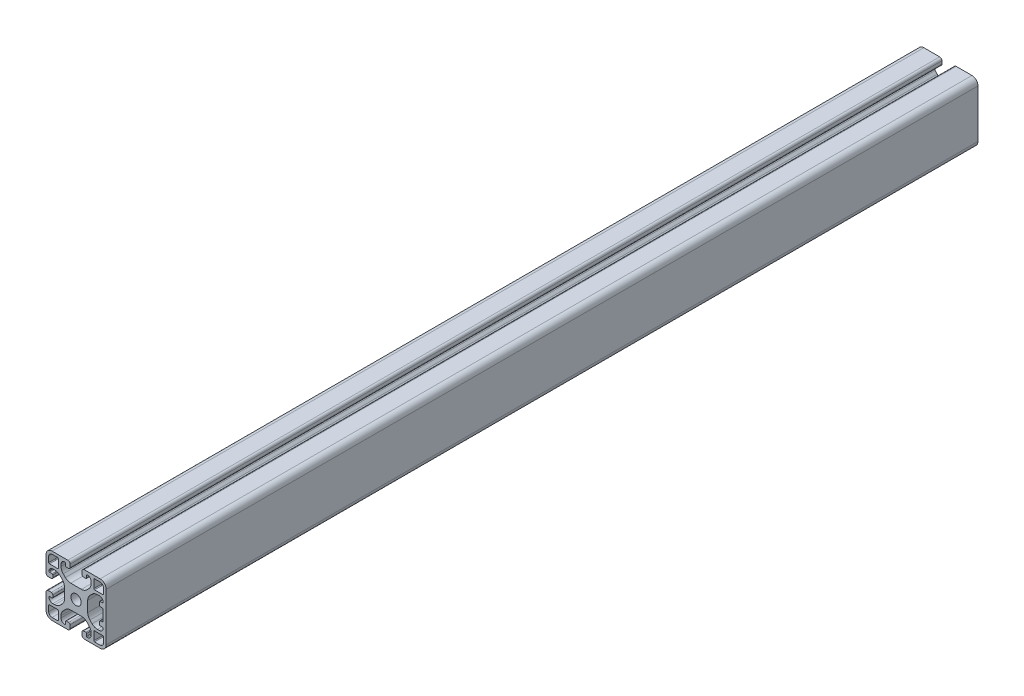
SolidWorks part; units mm, degrees
ref_plane "Piano frontale" through (0, 0, 0) normal (0, 0, 1) x (1, 0, 0)
ref_plane "Piano superiore" through (0, 0, 0) normal (0, 1, 0) x (1, 0, 0)
ref_plane "Piano destro" through (0, 0, 0) normal (1, 0, 0) x (0, 0, -1)
ref_plane "Piano1" through (0, 0, -340) normal (0, 0, -1) x (-1, 0, 0)
sketch "Schizzo1" plane through (0, 0, -340) normal (0, 0, -1) x (-1, 0, 0)
  line L0 (-12.3, -18.2) -> (-16, -18.2)
  line L1 (-18.2, -16) -> (-18.2, -12.3)
  line L2 (-17.7, -11.8) -> (-12.3, -11.8)
  line L3 (-11.8, -12.3) -> (-11.8, -17.7)
  line L4 (-11.8, 17.7) -> (-11.8, 12.3)
  line L5 (-12.3, 11.8) -> (-17.7, 11.8)
  line L6 (-18.2, 12.3) -> (-18.2, 16)
  line L7 (-16, 18.2) -> (-12.3, 18.2)
  line L8 (18.2, 16) -> (18.2, 12.3)
  line L9 (17.7, 11.8) -> (12.3, 11.8)
  line L10 (11.8, 12.3) -> (11.8, 17.7)
  line L11 (12.3, 18.2) -> (16, 18.2)
  line L12 (6.5, -15.5) -> (5, -15.5)
  line L13 (4, -16.5) -> (4, -18.5)
  line L14 (5.5, -20) -> (16, -20)
  line L15 (20, -16) -> (20, -5.5)
  line L16 (18.5, -4) -> (16.5, -4)
  line L17 (15.5, -5) -> (15.5, -6.5)
  line L18 (16, -7) -> (17.55, -7)
  line L19 (18, -7.45) -> (18, -7.5)
  line L20 (15.5, -10) -> (14.1924, -10)
  line L21 (10.6569, -8.5355) -> (9.2145, -7.0931)
  line L22 (7.75, -3.5576) -> (7.75, 3.5576)
  line L23 (9.2145, 7.0931) -> (10.6569, 8.5355)
  line L24 (14.1924, 10) -> (15.5, 10)
  line L25 (18, 7.5) -> (18, 7.45)
  line L26 (17.55, 7) -> (16, 7)
  line L27 (15.5, 6.5) -> (15.5, 5)
  line L28 (16.5, 4) -> (18.5, 4)
  line L29 (20, 5.5) -> (20, 16)
  line L30 (16, 20) -> (5.5, 20)
  line L31 (4, 18.5) -> (4, 16.5)
  line L32 (5, 15.5) -> (6.5, 15.5)
  line L33 (7, 16) -> (7, 17.55)
  line L34 (7.45, 18) -> (7.5, 18)
  line L35 (10, 15.5) -> (10, 14.1924)
  line L36 (8.5355, 10.6569) -> (7.0931, 9.2145)
  line L37 (3.5576, 7.75) -> (-3.5576, 7.75)
  line L38 (-7.0931, 9.2145) -> (-8.5355, 10.6569)
  line L39 (-10, 14.1924) -> (-10, 15.5)
  line L40 (-7.5, 18) -> (-7.45, 18)
  line L41 (-7, 17.55) -> (-7, 16)
  line L42 (-6.5, 15.5) -> (-5, 15.5)
  line L43 (-4, 16.5) -> (-4, 18.5)
  line L44 (-5.5, 20) -> (-16, 20)
  line L45 (-20, 16) -> (-20, -16)
  line L46 (-16, -20) -> (-5.5, -20)
  line L47 (-4, -18.5) -> (-4, -16.5)
  line L48 (-5, -15.5) -> (-6.5, -15.5)
  line L49 (-7, -16) -> (-7, -17.55)
  line L50 (-7.45, -18) -> (-7.5, -18)
  line L51 (-10, -15.5) -> (-10, -14.1924)
  line L52 (-8.5355, -10.6569) -> (-7.0931, -9.2145)
  line L53 (-3.5576, -7.75) -> (3.5576, -7.75)
  line L54 (7.0931, -9.2145) -> (8.5355, -10.6569)
  line L55 (10, -14.1924) -> (10, -15.5)
  line L56 (7.5, -18) -> (7.45, -18)
  line L57 (7, -17.55) -> (7, -16)
  line L58 (18.2, -12.3) -> (18.2, -16)
  line L59 (16, -18.2) -> (12.3, -18.2)
  line L60 (11.8, -17.7) -> (11.8, -12.3)
  line L61 (12.3, -11.8) -> (17.7, -11.8)
  line L62 (-16, 7) -> (-17.5, 7)
  line L63 (-15.5, 10) -> (-14.1924, 10)
  line L64 (-10.6569, 8.5355) -> (-9.2145, 7.0931)
  line L65 (-7.75, 3.5576) -> (-7.75, -3.5576)
  line L66 (-9.2145, -7.0931) -> (-10.6569, -8.5355)
  line L67 (-14.1924, -10) -> (-15.5, -10)
  line L68 (-17.5, -7) -> (-16, -7)
  line L69 (-15.5, -6.5) -> (-15.5, -5)
  line L70 (-16.5, -4) -> (-17.5, -4)
  line L71 (-18, -3.5) -> (-18, 3.5)
  line L72 (-17.5, 4) -> (-16.5, 4)
  line L73 (-15.5, 5) -> (-15.5, 6.5)
  arc A0 (-16, -18.2) -> (-18.2, -16) centre (-16, -16) cw
  arc A1 (-18.2, -12.3) -> (-17.7, -11.8) centre (-17.7, -12.3) cw
  arc A2 (-12.3, -11.8) -> (-11.8, -12.3) centre (-12.3, -12.3) cw
  arc A3 (-11.8, -17.7) -> (-12.3, -18.2) centre (-12.3, -17.7) cw
  arc A4 (-12.3, 18.2) -> (-11.8, 17.7) centre (-12.3, 17.7) cw
  arc A5 (-11.8, 12.3) -> (-12.3, 11.8) centre (-12.3, 12.3) cw
  arc A6 (-17.7, 11.8) -> (-18.2, 12.3) centre (-17.7, 12.3) cw
  arc A7 (-18.2, 16) -> (-16, 18.2) centre (-16, 16) cw
  arc A8 (16, 18.2) -> (18.2, 16) centre (16, 16) cw
  arc A9 (18.2, 12.3) -> (17.7, 11.8) centre (17.7, 12.3) cw
  arc A10 (12.3, 11.8) -> (11.8, 12.3) centre (12.3, 12.3) cw
  arc A11 (11.8, 17.7) -> (12.3, 18.2) centre (12.3, 17.7) cw
  arc A12 (5, -15.5) -> (4, -16.5) centre (5, -16.5) ccw
  arc A13 (4, -18.5) -> (5.5, -20) centre (5.5, -18.5) ccw
  arc A14 (16, -20) -> (20, -16) centre (16, -16) ccw
  arc A15 (20, -5.5) -> (18.5, -4) centre (18.5, -5.5) ccw
  arc A16 (16.5, -4) -> (15.5, -5) centre (16.5, -5) ccw
  arc A17 (15.5, -6.5) -> (16, -7) centre (16, -6.5) ccw
  arc A18 (17.55, -7) -> (18, -7.45) centre (17.55, -7.45) cw
  arc A19 (18, -7.5) -> (15.5, -10) centre (15.5, -7.5) cw
  arc A20 (14.1924, -10) -> (10.6569, -8.5355) centre (14.1924, -5) cw
  arc A21 (9.2145, -7.0931) -> (7.75, -3.5576) centre (12.75, -3.5576) cw
  arc A22 (7.75, 3.5576) -> (9.2145, 7.0931) centre (12.75, 3.5576) cw
  arc A23 (10.6569, 8.5355) -> (14.1924, 10) centre (14.1924, 5) cw
  arc A24 (15.5, 10) -> (18, 7.5) centre (15.5, 7.5) cw
  arc A25 (18, 7.45) -> (17.55, 7) centre (17.55, 7.45) cw
  arc A26 (16, 7) -> (15.5, 6.5) centre (16, 6.5) ccw
  arc A27 (15.5, 5) -> (16.5, 4) centre (16.5, 5) ccw
  arc A28 (18.5, 4) -> (20, 5.5) centre (18.5, 5.5) ccw
  arc A29 (20, 16) -> (16, 20) centre (16, 16) ccw
  arc A30 (5.5, 20) -> (4, 18.5) centre (5.5, 18.5) ccw
  arc A31 (4, 16.5) -> (5, 15.5) centre (5, 16.5) ccw
  arc A32 (6.5, 15.5) -> (7, 16) centre (6.5, 16) ccw
  arc A33 (7, 17.55) -> (7.45, 18) centre (7.45, 17.55) cw
  arc A34 (7.5, 18) -> (10, 15.5) centre (7.5, 15.5) cw
  arc A35 (10, 14.1924) -> (8.5355, 10.6569) centre (5, 14.1924) cw
  arc A36 (7.0931, 9.2145) -> (3.5576, 7.75) centre (3.5576, 12.75) cw
  arc A37 (-3.5576, 7.75) -> (-7.0931, 9.2145) centre (-3.5576, 12.75) cw
  arc A38 (-8.5355, 10.6569) -> (-10, 14.1924) centre (-5, 14.1924) cw
  arc A39 (-10, 15.5) -> (-7.5, 18) centre (-7.5, 15.5) cw
  arc A40 (-7.45, 18) -> (-7, 17.55) centre (-7.45, 17.55) cw
  arc A41 (-7, 16) -> (-6.5, 15.5) centre (-6.5, 16) ccw
  arc A42 (-5, 15.5) -> (-4, 16.5) centre (-5, 16.5) ccw
  arc A43 (-4, 18.5) -> (-5.5, 20) centre (-5.5, 18.5) ccw
  arc A44 (-16, 20) -> (-20, 16) centre (-16, 16) ccw
  arc A45 (-20, -16) -> (-16, -20) centre (-16, -16) ccw
  arc A46 (-5.5, -20) -> (-4, -18.5) centre (-5.5, -18.5) ccw
  arc A47 (-4, -16.5) -> (-5, -15.5) centre (-5, -16.5) ccw
  arc A48 (-6.5, -15.5) -> (-7, -16) centre (-6.5, -16) ccw
  arc A49 (-7, -17.55) -> (-7.45, -18) centre (-7.45, -17.55) cw
  arc A50 (-7.5, -18) -> (-10, -15.5) centre (-7.5, -15.5) cw
  arc A51 (-10, -14.1924) -> (-8.5355, -10.6569) centre (-5, -14.1924) cw
  arc A52 (-7.0931, -9.2145) -> (-3.5576, -7.75) centre (-3.5576, -12.75) cw
  arc A53 (3.5576, -7.75) -> (7.0931, -9.2145) centre (3.5576, -12.75) cw
  arc A54 (8.5355, -10.6569) -> (10, -14.1924) centre (5, -14.1924) cw
  arc A55 (10, -15.5) -> (7.5, -18) centre (7.5, -15.5) cw
  arc A56 (7.45, -18) -> (7, -17.55) centre (7.45, -17.55) cw
  arc A57 (7, -16) -> (6.5, -15.5) centre (6.5, -16) ccw
  arc A58 (17.7, -11.8) -> (18.2, -12.3) centre (17.7, -12.3) cw
  arc A59 (18.2, -16) -> (16, -18.2) centre (16, -16) cw
  arc A60 (12.3, -18.2) -> (11.8, -17.7) centre (12.3, -17.7) cw
  arc A61 (11.8, -12.3) -> (12.3, -11.8) centre (12.3, -12.3) cw
  circle A62 centre (0, 0) radius 3.4
  arc A63 (-15.5, 6.5) -> (-16, 7) centre (-16, 6.5) ccw
  arc A64 (-17.5, 7) -> (-18, 7.5) centre (-17.5, 7.5) cw
  arc A65 (-18, 7.5) -> (-15.5, 10) centre (-15.5, 7.5) cw
  arc A66 (-14.1924, 10) -> (-10.6569, 8.5355) centre (-14.1924, 5) cw
  arc A67 (-9.2145, 7.0931) -> (-7.75, 3.5576) centre (-12.75, 3.5576) cw
  arc A68 (-7.75, -3.5576) -> (-9.2145, -7.0931) centre (-12.75, -3.5576) cw
  arc A69 (-10.6569, -8.5355) -> (-14.1924, -10) centre (-14.1924, -5) cw
  arc A70 (-15.5, -10) -> (-18, -7.5) centre (-15.5, -7.5) cw
  arc A71 (-18, -7.5) -> (-17.5, -7) centre (-17.5, -7.5) cw
  arc A72 (-16, -7) -> (-15.5, -6.5) centre (-16, -6.5) ccw
  arc A73 (-15.5, -5) -> (-16.5, -4) centre (-16.5, -5) ccw
  arc A74 (-17.5, -4) -> (-18, -3.5) centre (-17.5, -3.5) cw
  arc A75 (-18, 3.5) -> (-17.5, 4) centre (-17.5, 3.5) cw
  arc A76 (-16.5, 4) -> (-15.5, 5) centre (-16.5, 5) ccw
extrude "Estrusione-Estrusione1" add sketch "Schizzo1" against normal blind 580
